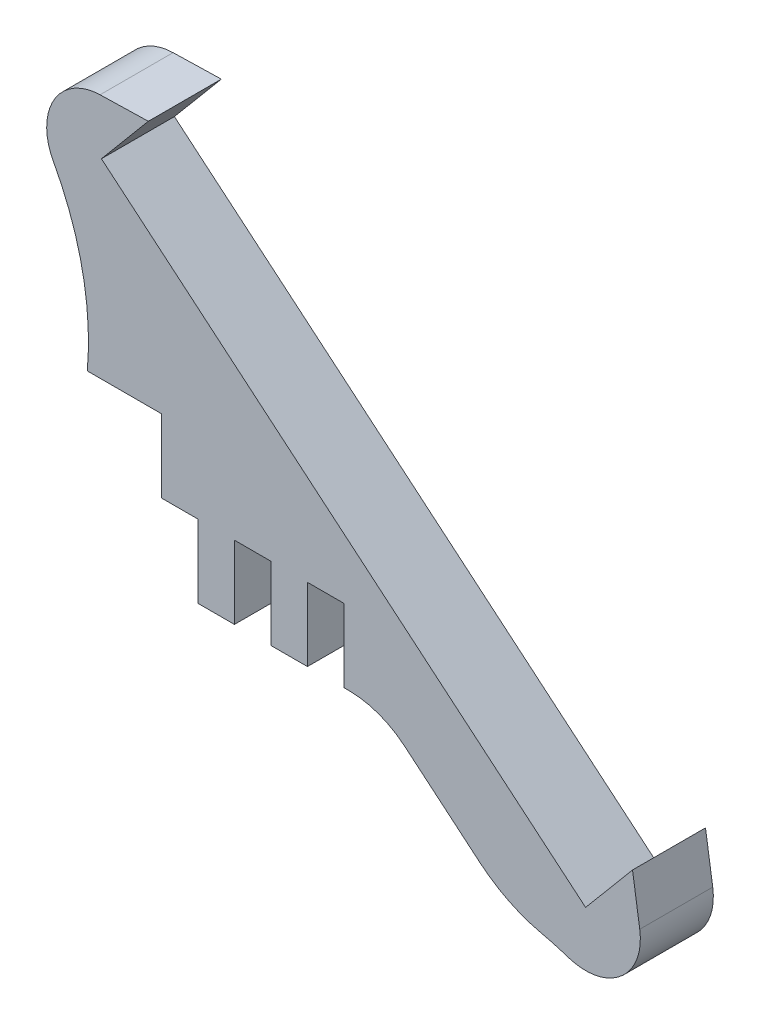
SolidWorks part; units mm, degrees
ref_plane "Front Plane" through (0, 0, 0) normal (0, 0, 1) x (1, 0, 0)
ref_plane "Top Plane" through (0, 0, 0) normal (0, 1, 0) x (1, 0, 0)
ref_plane "Right Plane" through (0, 0, 0) normal (1, 0, 0) x (0, 0, -1)
sketch "Sketch1" plane through (0, 0, 0) normal (0, 0, 1) x (1, 0, 0)
  line L0 (8.1421, 0) -> (11.3171, 0)
  line L1 (11.3171, 0) -> (11.3171, -6.35)
  line L2 (11.3171, -6.35) -> (14.4921, -6.35)
  line L3 (14.4921, -6.35) -> (14.4921, 0)
  line L4 (14.4921, 0) -> (17.6671, 0)
  line L5 (17.6671, 0) -> (17.6671, -6.35)
  line L6 (17.6671, -6.35) -> (20.8421, -6.35)
  line L7 (20.8421, -6.35) -> (20.8421, 0)
  line L8 (20.8421, 0) -> (24.0171, 0)
  line L9 (24.0171, 0) -> (24.0171, -6.35)
  line L10 (24.0171, -6.35) -> (24.4186, -6.35)
  line L11 (2.9186, 22.951) -> (7.0003, 27.8154)
  line L12 (45.0442, -12.3966) -> (49.1259, -7.5322)
  line L13 (23.9814, 5.2772) -> (28.5147, 10.6798) construction
  line L14 (49.1259, -7.5322) -> (49.7533, -11.6852)
  line L15 (1.7921, 0) -> (11.3171, 0) construction
  line L16 (1.6927, 6.35) -> (8.1421, 6.35)
  line L17 (1.7921, 6.35) -> (11.3171, 6.35) construction
  line L18 (8.1421, 6.35) -> (8.1421, 0)
  line L20 (7.0003, 27.8154) -> (2.8015, 27.712)
  line L21 (29.3167, -8.1327) -> (35.8298, -13.5979)
  line L24 (45.0442, -12.3966) -> (2.9186, 22.951)
  arc A0 (-1.2698, 20.6841) -> (1.6927, 6.35) centre (-23.6079, 8.5942) cw
  arc A1 (43.5391, -16.915) -> (41.1661, -16.2505) centre (35.5118, -41.0132) ccw
  arc A2 (2.8015, 27.712) -> (-1.2698, 20.6841) centre (2.9186, 22.951) ccw
  arc A3 (49.7533, -11.6852) -> (43.5391, -16.915) centre (45.0442, -12.3966) cw
  arc A4 (41.1661, -16.2505) -> (35.8298, -13.5979) centre (43.9932, -3.8692) cw
  arc A5 (24.4186, -6.35) -> (29.3167, -8.1327) centre (24.4186, -13.97) cw
  point P35 (27.1921, -6.35)
  dimension "D8" = 25.4
  dimension "D2" = 6.35
  dimension "D9" = 6.35
  dimension "D10" = 54.991
  dimension "D12" = 12.7
  dimension "D14" = 7.62
  dimension "D3" = 3.175
  dimension "D4" = 3.175
  dimension "D5" = 3.175
  dimension "D6" = 3.175
  dimension "D7" = 3.175
  dimension "D11" = 6.35
  dimension "D13" = 6.35
extrude "Boss-Extrude1" add sketch "Sketch1" along normal blind 6.35
